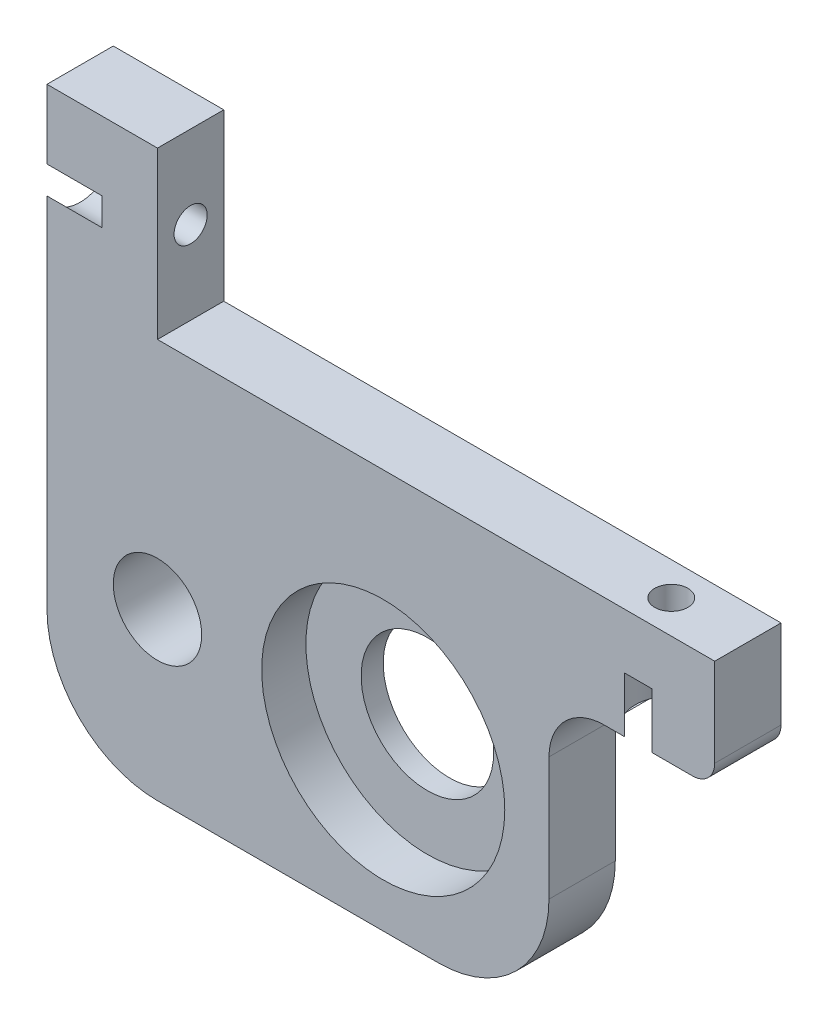
SolidWorks part; units mm, degrees
ref_plane "Alzado" through (0, 0, 0) normal (0, 0, 1) x (1, 0, 0)
ref_plane "Planta" through (0, 0, 0) normal (0, 1, 0) x (1, 0, 0)
ref_plane "Vista lateral" through (0, 0, 0) normal (1, 0, 0) x (0, 0, -1)
sketch "Croquis1" plane through (0, 0, 0) normal (0, 0, 1) x (1, 0, 0)
  line L0 (-50.43, 0) -> (0, 0)
  line L1 (0, 0) -> (0, -8)
  line L2 (-2, -10) -> (-10, -10)
  line L3 (-15, -15) -> (-15, -26.15)
  line L4 (-25, -36.15) -> (-50.43, -36.15)
  line L5 (-60.43, -26.15) -> (-60.43, 15)
  line L6 (-60.43, 15) -> (-50.43, 15)
  line L7 (-50.43, 15) -> (-50.43, 0)
  circle A0 centre (-50.43, -21.15) radius 4
  circle A1 centre (-30, -21.15) radius 6
  circle A2 centre (-30, -21.15) radius 11
  arc A3 (-50.43, -36.15) -> (-60.43, -26.15) centre (-50.43, -26.15) cw
  arc A4 (-25, -36.15) -> (-15, -26.15) centre (-25, -26.15) ccw
  arc A5 (-15, -15) -> (-10, -10) centre (-10, -15) cw
  arc A6 (0, -8) -> (-2, -10) centre (-2, -8) cw
  dimension "D1" = 8
  dimension "D3" = 20.43
  dimension "D4" = 12
  dimension "D7" = 22
  dimension "D14" = 10
  dimension "D15" = 10
  dimension "D16" = 5
  dimension "D17" = 2
  dimension "D2" = 10
  dimension "D5" = 10
  dimension "D8" = 21.15
  dimension "D9" = 15
  dimension "D10" = 15
  dimension "D11" = 10
  dimension "D12" = 15
  dimension "D13" = 15
extrude "Saliente-Extruir2" add sketch "Croquis1" along normal blind 6 contours A1 | A0 | L4 A3 L5 L6 L7 L0 L1 A6 L2 A5 L3 A4
sketch "Croquis2" plane through (0, 0, 6) normal (0, 0, 1) x (1, 0, 0)
  circle A0 centre (-30, -21.15) radius 11
  dimension "D1" = 22
extrude "Cortar-Extruir1" cut sketch "Croquis2" against normal blind 4
sketch "Croquis3" plane through (0, 0, 0) normal (0, 1, 0) x (-1, 0, 0)
  line L1 (50.43, 0) -> (0, 0) construction
  line L2 (50.43, 6) -> (50.43, 0) construction
  circle A0 centre (6.93, 3) radius 1.5
  dimension "D1" = 3
  dimension "D3" = 3
  dimension "D2" = 43.5
extrude "Cortar-Extruir2" cut sketch "Croquis3" against normal through all
sketch "Croquis4" plane through (-50.43, 0, 0) normal (1, 0, 0) x (0, 0, -1)
  line L0 (-6, 15) -> (0, 15) construction
  line L1 (-6, 15) -> (-6, 0) construction
  circle A0 centre (-3, 7.5) radius 1.5
  dimension "D1" = 7.5
  dimension "D2" = 3
  dimension "D3" = 3
extrude "Cortar-Extruir3" cut sketch "Croquis4" against normal through all
sketch "Croquis5" plane through (-60.43, 0, 0) normal (-1, 0, 0) x (0, 0, 1)
  circle A0 centre (3, 7.5) radius 3.25
  dimension "D1" = 6.5
extrude "Cortar-Extruir4" cut sketch "Croquis5" against normal blind 5
sketch "Croquis6" plane through (0, -10, 0) normal (0, -1, 0) x (1, 0, 0)
  circle A0 centre (-6.93, 3) radius 3.25
  dimension "D1" = 6.5
extrude "Cortar-Extruir5" cut sketch "Croquis6" against normal blind 5
ref_plane "Plano1" through (0, 17.5, 0) normal (0, 1, 0) x (1, 0, 0)
